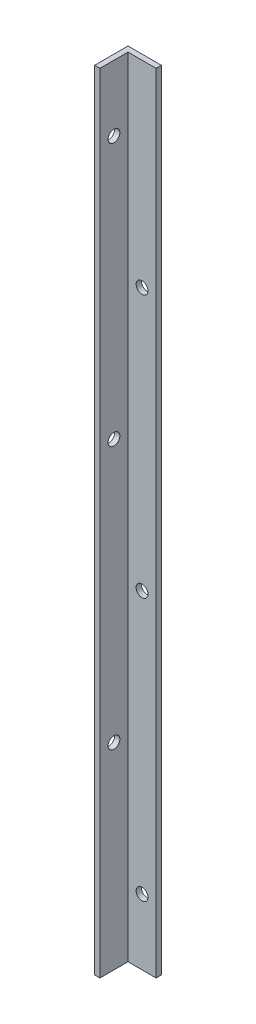
SolidWorks part; units mm, degrees
material "Alumina"
ref_plane "Front Plane" through (0, 0, 0) normal (0, 0, 1) x (1, 0, 0)
ref_plane "Top Plane" through (0, 0, 0) normal (0, 1, 0) x (1, 0, 0)
ref_plane "Right Plane" through (0, 0, 0) normal (1, 0, 0) x (0, 0, -1)
sketch "Sketch1" plane through (0, 0, 0) normal (0, 1, 0) x (1, 0, 0)
  line L0 (0, 0) -> (0, -12.7)
  line L1 (0, 0) -> (12.7, 0)
  line L2 (2, -2) -> (2, -12.7)
  line L3 (2, -2) -> (12.7, -2)
  line L4 (0, -12.7) -> (2, -12.7)
  line L5 (12.7, -2) -> (12.7, 0)
  dimension "D1" = 12.7
  dimension "D2" = 12.7
  dimension "D3" = 2
extrude "Boss-Extrude1" add sketch "Sketch1" along normal blind 300
sketch "Sketch2" plane through (2, 0, 0) normal (1, 0, 0) x (0, 0, -1)
  line L0 (-7.35, 300) -> (-7.35, 0) construction
  line L1 (-12.7, 300) -> (-2, 300) construction
  line L2 (-12.7, 0) -> (-2, 0) construction
  circle A0 centre (-7.35, 275) radius 2.25
  circle A1 centre (-7.35, 175) radius 2.25
  circle A2 centre (-7.35, 75) radius 2.25
  dimension "D2" = 4.5
  dimension "D1" = 25
extrude "Cut-Extrude1" cut sketch "Sketch2" against normal blind 10
sketch "Sketch3" plane through (0, 0, 2) normal (0, 0, 1) x (1, 0, 0)
  line L0 (7.35, 300) -> (7.35, 0) construction
  line L1 (2, 300) -> (12.7, 300) construction
  line L2 (2, 0) -> (12.7, 0) construction
  circle A0 centre (7.35, 225) radius 2.25
  circle A1 centre (7.35, 125) radius 2.25
  circle A2 centre (7.35, 25) radius 2.25
  dimension "D2" = 4.5
  dimension "D1" = 75
extrude "Cut-Extrude2" cut sketch "Sketch3" against normal blind 10
